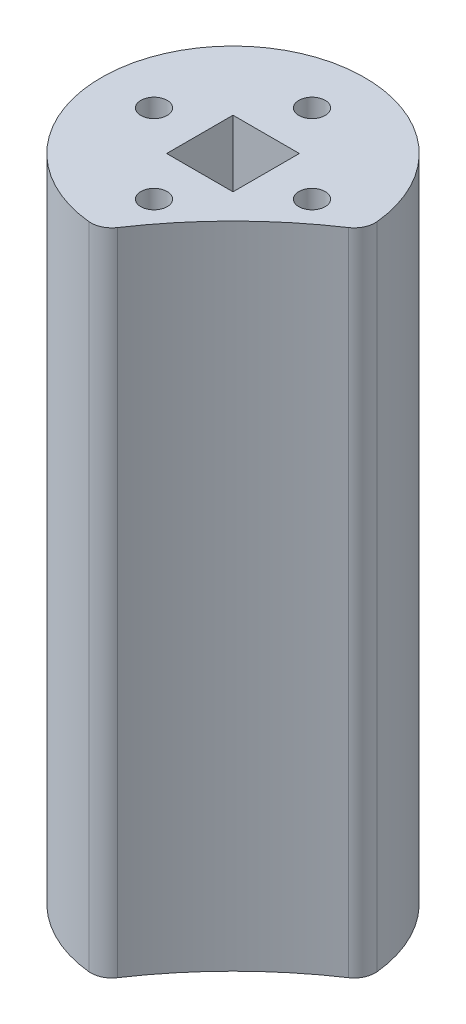
SolidWorks part; units mm, degrees
material "ABS"
ref_plane "Front Plane" through (0, 0, 0) normal (0, 0, 1) x (1, 0, 0)
ref_plane "Top Plane" through (0, 0, 0) normal (0, 1, 0) x (1, 0, 0)
ref_plane "Right Plane" through (0, 0, 0) normal (1, 0, 0) x (0, 0, -1)
sketch "Sketch1" plane through (0, 0, 0) normal (0, 1, 0) x (1, 0, 0)
  line L1 (-3.15, 3.15) -> (3.15, 3.15)
  line L2 (-3.15, 3.15) -> (-3.15, -3.15)
  line L3 (-3.15, -3.15) -> (3.15, -3.15)
  line L4 (3.15, 3.15) -> (3.15, -3.15)
  circle A0 centre (0, 0) radius 12.5
  circle A1 centre (0, 0) radius 7.5 construction
  circle A2 centre (0, 7.5) radius 1.5 construction
  circle A3 centre (7.5, 0) radius 1.5 construction
  circle A4 centre (0, -7.5) radius 1.5 construction
  circle A5 centre (-7.5, 0) radius 1.5 construction
  arc A6 (12.5, 0) -> (0, -12.5) centre (33.8351, -33.8351) ccw
  point P8 (0, 3.15)
  point P9 (-3.15, 0)
  point P21 (0, 0)
  dimension "D1" = 15
  dimension "D2" = 25
  dimension "D4" = 3
  dimension "D6" = 40
  dimension "D3" = 6.3
  dimension "D5" = 4
extrude "Boss-Extrude1" add sketch "Sketch1" against normal blind 61.675 contours A6 A0 L1 L4 L3 L2
hole_wizard "Tap Drill for M3x0.5 Tap1" positions "3DSketch1" profile "Sketch2" hole size "M3x0.5" standard "ANSI Metric" end condition up to next
sketch3d "3DSketch1"
  point P18 (0, 0, -7.5)
  point P20 (7.5, 0, 0)
  point P22 (-7.5, 0, 0)
  point P24 (0, 0, 7.5)
sketch "Sketch2" plane through (0, 0, -7.5) normal (1, 0, 0) x (0, 0, 1)
  line L0 (0, 0) -> (0, 61.675)
  line L1 (0, 61.675) -> (1.25, 61.675)
  line L2 (1.25, 61.675) -> (1.25, 0)
  line L5 (1.25, 0) -> (0, 0)
  line L11 (0, -6.35) -> (0, 107.95) construction
  dimension "Thru Hole Dia." = 2.5
  dimension "Thru Hole Depth" = 61.675
fillet "Fillet1" radius 2 2 edges at (0, -30.8375, 12.5) (12.5, -30.8375, 0)
